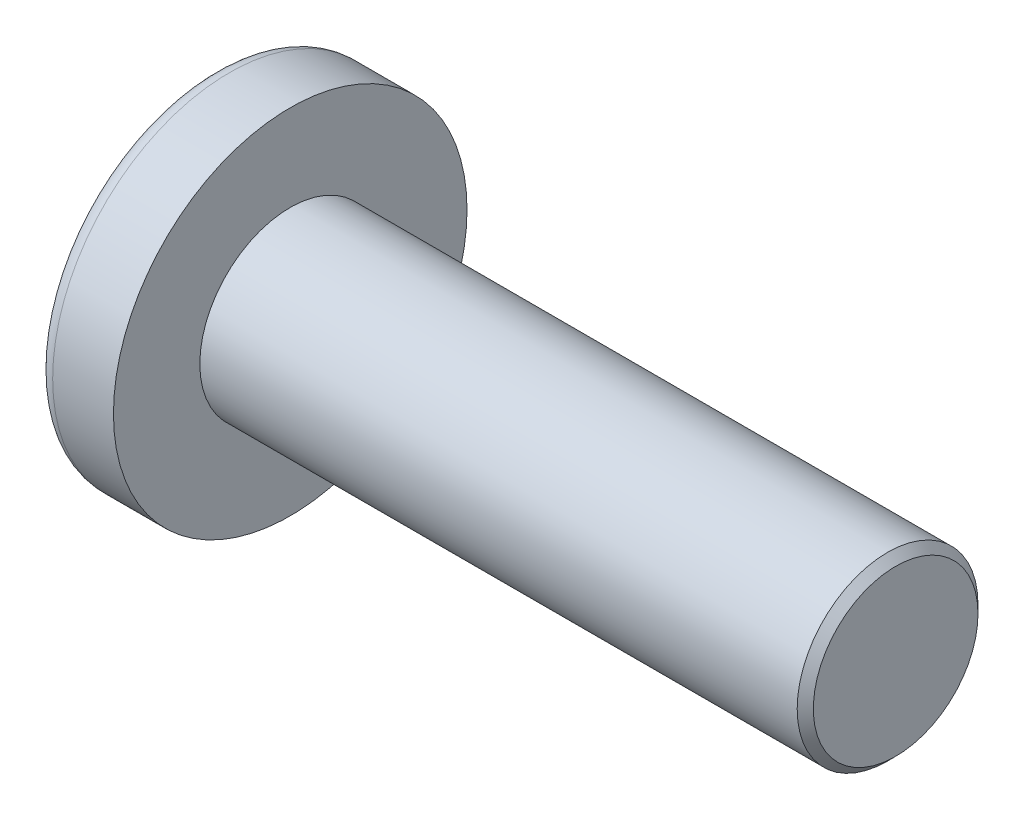
SolidWorks part; units mm, degrees
material "Alloy Steel"
ref_plane "Plane1" through (0, 0, 0) normal (0, 0, 1) x (1, 0, 0)
ref_plane "Plane2" through (0, 0, 0) normal (0, 1, 0) x (1, 0, 0)
ref_plane "Plane3" through (0, 0, 0) normal (1, 0, 0) x (0, 0, -1)
sketch "BodySke" plane through (0, 0, 0) normal (0, 0, 1) x (1, 0, 0)
  line L0 (2.032, 1.4224) -> (2.032, 2.7813)
  line L1 (2.3495, 6.35) -> (2.3495, -3.175) construction
  line L2 (-25.4, 0) -> (127, 0) construction
  line L3 (11.557, 0) -> (0, 0)
  line L4 (2.032, 1.4224) -> (11.557, 1.4224)
  line L5 (11.557, 1.4224) -> (11.557, 0)
  line L6 (1.0756, 2.7813) -> (2.032, 2.7813)
  line L7 (2.032, -1.4224) -> (11.557, -1.4224) construction
  line L8 (2.032, 6.35) -> (2.032, -3.175) construction
  arc A0 (0.8702, 2.6767) -> (0, 0) centre (4.5517, 0) ccw
  arc A2 (0.8702, 2.6767) -> (1.0756, 2.7813) centre (1.0756, 2.5273) cw
  dimension "Head_crown_rad" = 4.5517
  dimension "Head_fillet_rad" = 0.254
  dimension "Diameter" = 2.8448
  dimension "Length" = 9.525
  dimension "Head_ht" = 2.032
  dimension "Head_dia" = 5.5626
  dimension "Advance" = 0.635
  dimension "Thread_nom" = 9.525
revolve "Base-Revolve" add sketch "BodySke" angle 360 about L2
cosmetic thread "ThreadCosmetic" parameters "Thread_length"=8.89, "Thread_minor"=2.0879
sketch "Sketch3" plane through (0, 0, 0) normal (1, 0, 0) x (0, 0, -1)
  line L0 (0.4064, -1.8161) -> (-0.4064, -1.8161)
  line L1 (0.4064, -1.8161) -> (0.4064, 1.8161)
  line L2 (-0.4064, 1.8161) -> (0.4064, 1.8161)
  line L3 (-0.4064, 1.8161) -> (-0.4064, -1.8161)
  dimension "Cross_dia" = 3.6322
  dimension "D1" = 1.8161
  dimension "Cross_width" = 0.8128
  dimension "D2" = 0.4064
ref_plane "Plane4" through (2.0066, 0, 0) normal (1, 0, 0) x (0, 0, -1)
sketch "Sketch4" plane through (2.0066, 0, 0) normal (1, 0, 0) x (0, 0, -1)
  line L0 (0.2032, -0.2032) -> (-0.2032, -0.2032)
  line L1 (0.2032, -0.2032) -> (0.2032, 0.2032)
  line L2 (-0.2032, 0.2032) -> (0.2032, 0.2032)
  line L3 (-0.2032, 0.2032) -> (-0.2032, -0.2032)
  dimension "D2" = 0.4064
  dimension "D1" = 0.4064
  dimension "D3" = 0.2032
  dimension "D4" = 0.2032
loft "Cut-Loft1" cut profiles "Sketch3", "Sketch4"
pattern_circular "CirPattern1" count 2 every 90 about axis through (0, 0, 0) along (1, 0, 0) of "Cut-Loft1"
chamfer "Chamfer1" distance 0.127 angle 45 1 edges at (11.557, 0, 1.4224)
equation "\"D1@Sketch3\" = \"Cross_dia@Sketch3\" / 2"
equation "\"D2@Sketch3\" = \"Cross_width@Sketch3\" / 2"
equation "\"D1@Sketch4\" = \"Cross_width@Sketch3\" *.5"
equation "\"D2@Sketch4\" = \"D1@Sketch4\""
equation "\"D3@Sketch4\" = \"D1@Sketch4\" / 2"
equation "\"D4@Sketch4\" = \"D2@Sketch4\" / 2"
equation "\"Thread_length@ThreadCosmetic\" = ((sgn( (\"Length@BodySke\" - \"Advance@BodySke\" ) - \"Thread_nom@BodySke\" )-1)*( (\"Length@BodySke\" - \"Advance@BodySke\" ) - \"Thread_nom@BodySke\" ))/-2+ \"Thread_nom@BodySke\""
